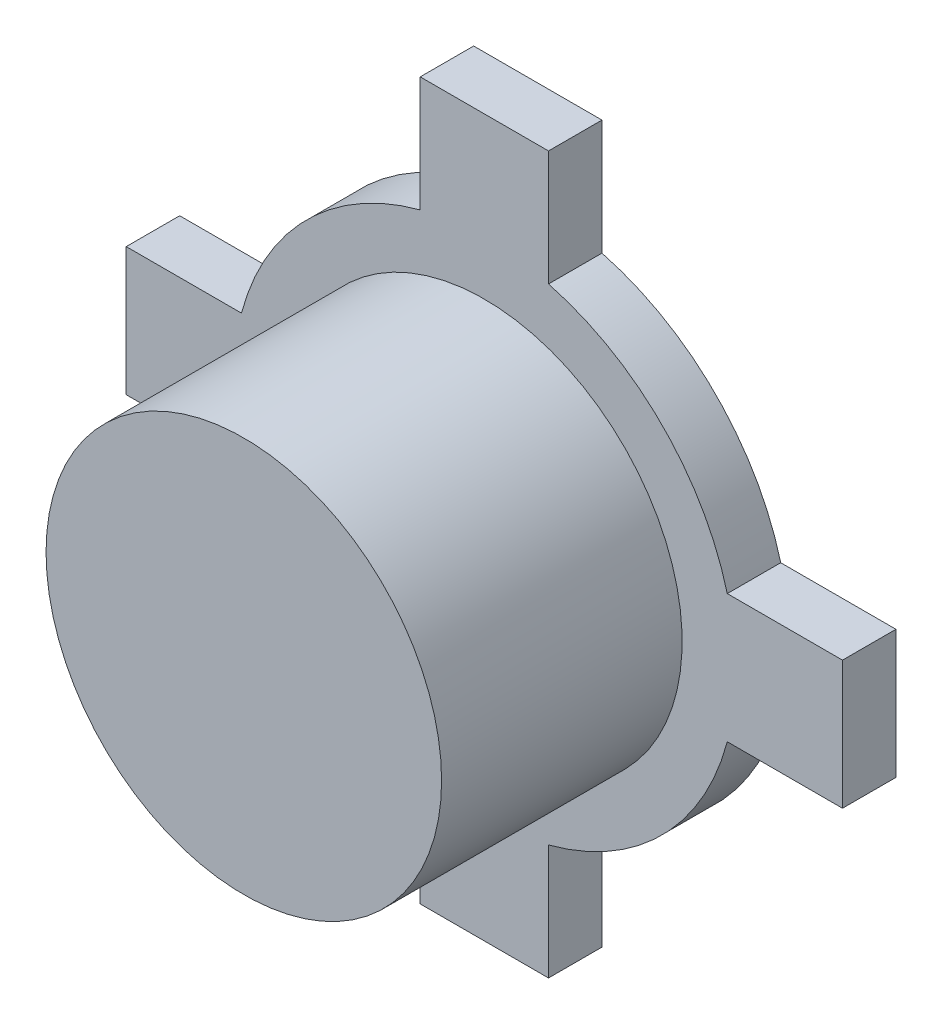
SolidWorks part; units mm, degrees
ref_plane "Front Plane" through (0, 0, 0) normal (0, 0, 1) x (1, 0, 0)
ref_plane "Top Plane" through (0, 0, 0) normal (0, 1, 0) x (1, 0, 0)
ref_plane "Right Plane" through (0, 0, 0) normal (1, 0, 0) x (0, 0, -1)
sketch "Sketch1" plane through (0, 0, 0) normal (0, 0, 1) x (1, 0, 0)
  circle A0 centre (0, 0) radius 3.7
  circle A1 centre (0, 0) radius 4 construction
  dimension "D1" = 0.3
extrude "Boss-Extrude1" add sketch "Sketch1" along normal blind 4.5
sketch "Sketch2" plane through (0, 0, 0) normal (0, 0, -1) x (-1, 0, 0)
  line L118 (-1.2, 6.7) -> (-1.2, 4.5442)
  line L119 (-4.5442, 1.2) -> (-6.7, 1.2)
  line L120 (-6.7, 1.2) -> (-6.7, -1.2)
  line L121 (-6.7, -1.2) -> (-4.5442, -1.2)
  line L122 (-1.2, -4.5442) -> (-1.2, -6.7)
  line L123 (-1.2, -6.7) -> (1.2, -6.7)
  line L124 (1.2, -6.7) -> (1.2, -4.5442)
  line L125 (4.5442, -1.2) -> (6.7, -1.2)
  line L126 (6.7, -1.2) -> (6.7, 1.2)
  line L127 (6.7, 1.2) -> (4.5442, 1.2)
  line L128 (1.2, 4.5442) -> (1.2, 6.7)
  line L129 (1.2, 6.7) -> (-1.2, 6.7)
  line L130 (-1.2, 6.7) -> (-1.2, 4.5442)
  line L131 (-4.5442, 1.2) -> (-6.7, 1.2)
  line L132 (-6.7, 1.2) -> (-6.7, -1.2)
  line L133 (-6.7, -1.2) -> (-4.5442, -1.2)
  line L134 (-1.2, -4.5442) -> (-1.2, -6.7)
  line L135 (-1.2, -6.7) -> (1.2, -6.7)
  line L136 (1.2, -6.7) -> (1.2, -4.5442)
  line L137 (4.5442, -1.2) -> (6.7, -1.2)
  line L138 (6.7, -1.2) -> (6.7, 1.2)
  line L139 (6.7, 1.2) -> (4.5442, 1.2)
  line L140 (1.2, 4.5442) -> (1.2, 6.7)
  line L141 (1.2, 6.7) -> (-1.2, 6.7)
  arc A37 (-1.2, 4.5442) -> (-4.5442, 1.2) centre (0, 0) ccw
  arc A38 (-4.5442, -1.2) -> (-1.2, -4.5442) centre (0, 0) ccw
  arc A39 (1.2, -4.5442) -> (4.5442, -1.2) centre (0, 0) ccw
  arc A40 (4.5442, 1.2) -> (1.2, 4.5442) centre (0, 0) ccw
  arc A41 (-1.2, 4.5442) -> (-4.5442, 1.2) centre (0, 0) ccw
  arc A42 (-4.5442, -1.2) -> (-1.2, -4.5442) centre (0, 0) ccw
  arc A43 (1.2, -4.5442) -> (4.5442, -1.2) centre (0, 0) ccw
  arc A44 (4.5442, 1.2) -> (1.2, 4.5442) centre (0, 0) ccw
  dimension "D1" = 0.3
extrude "Boss-Extrude2" add sketch "Sketch2" along normal blind 1
